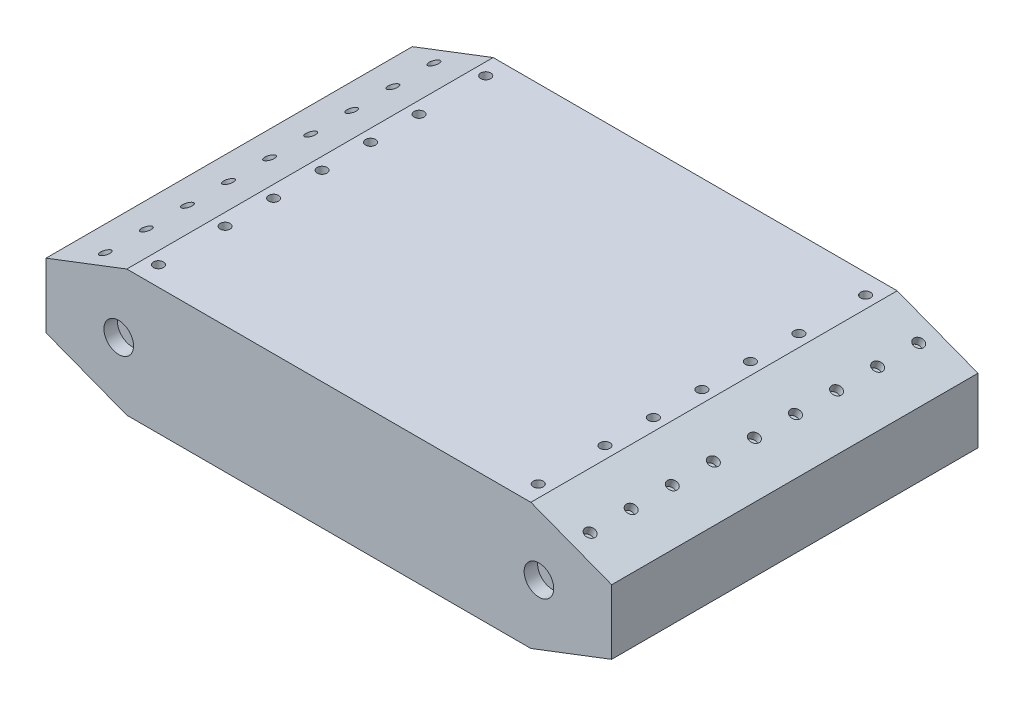
SolidWorks part; units mm, degrees
ref_plane "Front Plane" through (0, 0, 0) normal (0, 0, 1) x (1, 0, 0)
ref_plane "Top Plane" through (0, 0, 0) normal (0, 1, 0) x (1, 0, 0)
ref_plane "Right Plane" through (0, 0, 0) normal (1, 0, 0) x (0, 0, -1)
sketch "Sketch3" plane through (0, 0, 0) normal (0, 0, 1) x (1, 0, 0)
  line L0 (-75, 23.5) -> (-105, 12)
  line L1 (-75, 23.5) -> (75, 23.5)
  line L3 (-75, -23.5) -> (75, -23.5)
  line L5 (-105, 0) -> (105, 0) construction
  line L6 (0, 0) -> (0, 40.4518) construction
  line L7 (-105, 12) -> (-105, -12)
  line L8 (-105, -12) -> (-75, -23.5)
  line L9 (75, 23.5) -> (105, 12)
  line L10 (105, 12) -> (105, -12)
  line L11 (105, -12) -> (75, -23.5)
  line L12 (0, 0) -> (0, -47.2027) construction
  point P0 (0, 0)
  dimension "D1" = 47
  dimension "D2" = 210
  dimension "D3" = 30
  dimension "D4" = 24
extrude "Boss-Extrude1" add sketch "Sketch3" along normal blind 136
ref_plane "Plane1" through (0, 0, 136) normal (0, 0, 1) x (1, 0, 0)
ref_plane "Plane2" through (0, 0, 0) normal (0, 0, -1) x (-1, 0, 0)
sketch "Sketch5" plane through (0, 0, 136) normal (0, 0, 1) x (1, 0, 0)
  line L0 (-105, 0) -> (105, 0) construction
  line L1 (-105, 12) -> (-105, -12) construction
  line L2 (105, -12) -> (105, 12) construction
  line L3 (0, 0) -> (0, 23.5) construction
  line L4 (75, 23.5) -> (-75, 23.5) construction
  line L5 (0, 11.75) -> (105, 11.75) construction
  circle A0 centre (78, 0) radius 5.5
  circle A1 centre (-78, 0) radius 5.5
  dimension "D1" = 11
  dimension "D2" = 27
extrude "LeftWheels" cut sketch "Sketch5" against normal blind 5
sketch "Sketch6" plane through (0, 0, 0) normal (0, 0, -1) x (-1, 0, 0)
  line L0 (0, 37.9529) -> (0, -46.7634) construction
  circle A2 centre (78, 0) radius 5.5
  circle A4 centre (-78, 0) radius 5.5
  dimension "D1" = 11
extrude "RightWheels" cut sketch "Sketch6" against normal blind 5
sketch "Sketch7" plane through (17.4631, 45.5558, 0) normal (0.3579, 0.9337, 0) x (0.9337, -0.3579, 0)
  line L1 (93.7481, 0) -> (61.6195, 0) construction
  line L2 (61.6195, 0) -> (93.7481, 0) construction
  line L3 (77.6838, 0) -> (77.6838, -136) construction
  line L4 (93.7481, -136) -> (61.6195, -136) construction
  circle A0 centre (77.6838, -7) radius 1.9
  circle A1 centre (77.6838, -22.25) radius 1.9
  circle A2 centre (77.6838, -37.5) radius 1.9
  circle A3 centre (77.6838, -52.75) radius 1.9
  circle A4 centre (77.6838, -68) radius 1.9
  circle A5 centre (77.6838, -83.25) radius 1.9
  circle A6 centre (77.6838, -98.5) radius 1.9
  circle A7 centre (77.6838, -113.75) radius 1.9
  circle A8 centre (77.6838, -129) radius 1.9
  dimension "D1" = 3.8
  dimension "D3" = 3.8
  dimension "D5" = 3.8
  dimension "D6" = 3.8
  dimension "D7" = 3.8
  dimension "D8" = 3.8
  dimension "D9" = 3.8
  dimension "D10" = 3.8
  dimension "D11" = 3.8
  dimension "D14" = 15.25
  dimension "D2" = 7
  dimension "D4" = 15.25
  dimension "D12" = 15.25
  dimension "D13" = 15.25
  dimension "D15" = 15.25
  dimension "D16" = 15.25
  dimension "D17" = 15.25
  dimension "D18" = 15.25
extrude "FrontHoles" cut sketch "Sketch7" against normal blind 3
mirror "BackHoles" about plane through (0, 0, 0) normal (1, 0, 0) of "FrontHoles"
sketch "Sketch8" plane through (0, 23.5, 0) normal (0, 1, 0) x (1, 0, 0)
  line L0 (75, 0) -> (-75, 0) construction
  line L1 (75, -136) -> (75, 0) construction
  line L2 (75, -136) -> (-75, -136) construction
  line L3 (0, 22.3575) -> (0, -153.2582) construction
  circle A0 centre (70.5, -7.25) radius 1.85
  circle A1 centre (70.5, -32) radius 1.85
  circle A2 centre (70.5, -50) radius 1.85
  circle A3 centre (70.5, -68) radius 1.85
  circle A4 centre (70.5, -86) radius 1.85
  circle A5 centre (70.5, -104) radius 1.85
  circle A6 centre (70.5, -128.75) radius 1.85
  circle A7 centre (-70.5, -128.75) radius 1.85
  circle A8 centre (-70.5, -104) radius 1.85
  circle A9 centre (-70.5, -86) radius 1.85
  circle A10 centre (-70.5, -68) radius 1.85
  circle A11 centre (-70.5, -50) radius 1.85
  circle A12 centre (-70.5, -32) radius 1.85
  circle A13 centre (-70.5, -7.25) radius 1.85
  dimension "D2" = 3.7
  dimension "D3" = 4.5
  dimension "D4" = 3.7
  dimension "D7" = 3.7
  dimension "D1" = 7.25
  dimension "D5" = 24.75
  dimension "D8" = 4.5
  dimension "D9" = 7.25
  dimension "D10" = 4.5
  dimension "D11" = 24.75
  dimension "D12" = 18
  dimension "D6" = 5
extrude "TopHoles" cut sketch "Sketch8" against normal blind 3
